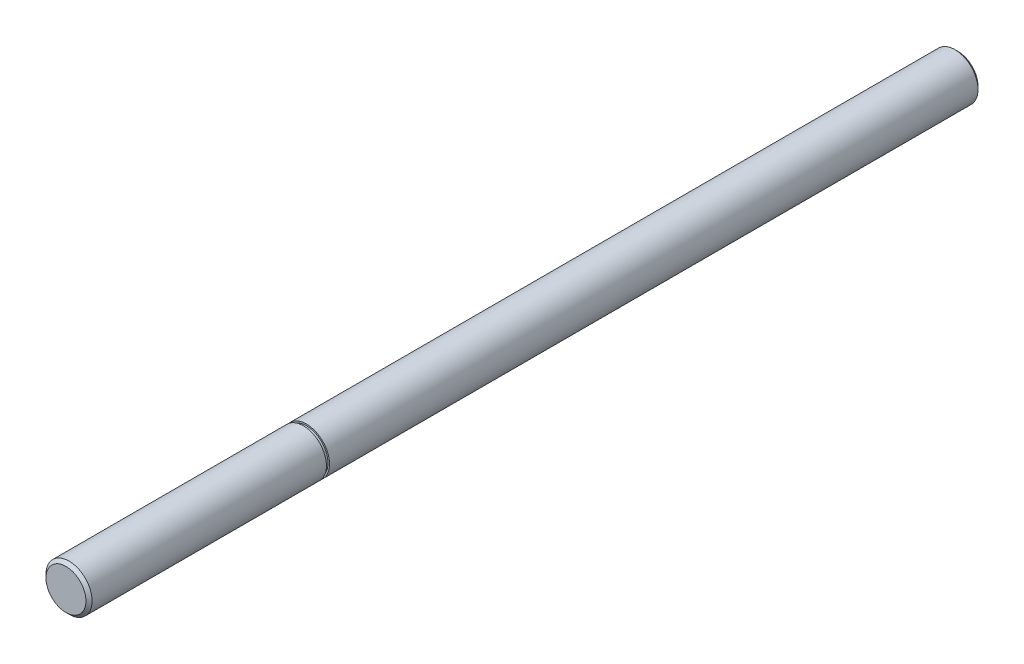
SolidWorks part; units mm, degrees
material "Alumina"
ref_plane "Front Plane" through (0, 0, 0) normal (0, 0, 1) x (1, 0, 0)
ref_plane "Top Plane" through (0, 0, 0) normal (0, 1, 0) x (1, 0, 0)
ref_plane "Right Plane" through (0, 0, 0) normal (1, 0, 0) x (0, 0, -1)
sketch "Sketch1" plane through (0, 0, 0) normal (0, 0, 1) x (1, 0, 0)
  circle A0 centre (0, 0) radius 7.5
  dimension "D1" = 15
extrude "Boss-Extrude1" add sketch "Sketch1" along normal blind 290
chamfer "Chamfer1" distance 1 angle 45 2 edges at (7.5, 0, 0) (7.5, 0, 290)
sketch3d "3DSketch2" plane through (0, 0, 0) normal (0, 0, 1) x (1, 0, 0)
  dimension "D1" = 212.82
sketch "Sketch2" plane through (0, 0, 212.82) normal (0, 0, 1) x (1, 0, 0)
  circle A0 centre (0, 0) radius 7
  circle A1 centre (0, 0) radius 7.5
  dimension "D1" = 14
  dimension "D2" = 15
extrude "Cut-Extrude1" cut sketch "Sketch2" against normal blind 1
